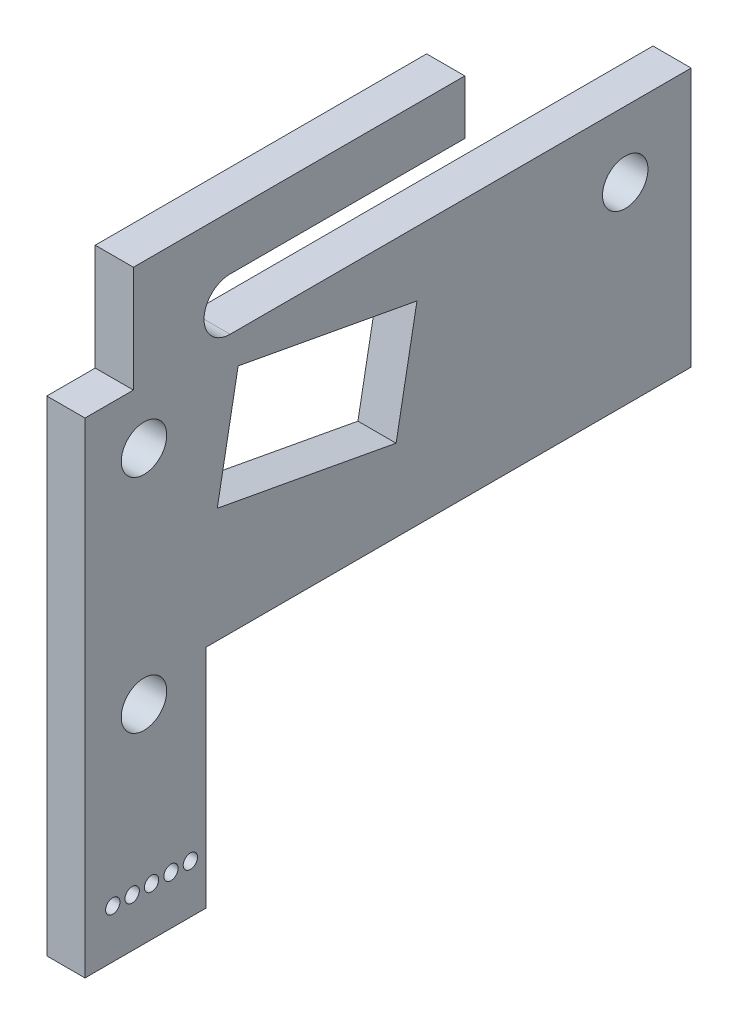
SolidWorks part; units mm, degrees
material "Hardboard"
ref_plane "Front Plane" through (0, 0, 0) normal (0, 0, 1) x (1, 0, 0)
ref_plane "Top Plane" through (0, 0, 0) normal (0, 1, 0) x (1, 0, 0)
ref_plane "Right Plane" through (0, 0, 0) normal (1, 0, 0) x (0, 0, -1)
sketch "Sketch1" plane through (0, 0, 0) normal (1, 0, 0) x (0, 0, -1)
  line L0 (-56.5904, 6.9096) -> (-51.5186, 6.9096)
  line L1 (-56.5904, 6.9096) -> (-56.5904, -43.8904)
  line L2 (-56.5904, -43.8904) -> (-43.8904, -43.8904)
  line L3 (-43.8904, -43.8904) -> (-43.8904, -20.2221)
  line L4 (-43.8904, -20.2221) -> (6.9096, -20.2221)
  line L5 (6.9096, -20.2221) -> (6.9096, 6.9096)
  line L6 (0, 6.9096) -> (0, 0) construction
  line L7 (6.9096, 0) -> (0, 0) construction
  line L8 (-40.5479, 3.6124) -> (-21.8156, 0.1475)
  line L9 (-40.5479, 3.6124) -> (-42.7334, -8.2033)
  line L10 (-21.8156, 0.1475) -> (-24.0012, -11.6682)
  line L11 (-42.7334, -8.2033) -> (-24.0012, -11.6682)
  line L12 (-45.553, -38.8104) -> (-47.585, -38.8104) construction
  line L13 (-41.3883, 12.3738) -> (-16.804, 12.3738)
  line L14 (-16.804, 12.3738) -> (-16.804, 18.0537)
  line L15 (-16.804, 18.0537) -> (-51.5186, 18.0537)
  line L16 (-51.5186, 18.0537) -> (-51.5186, 6.9096)
  line L17 (-41.3883, 6.9096) -> (6.9096, 6.9096)
  line L18 (-43.4375, 2.8639) -> (-40.7623, 15.279) construction
  circle A0 centre (0, 0) radius 2.3813
  circle A1 centre (-45.553, -38.8104) radius 0.75
  circle A2 centre (-47.585, -38.8104) radius 0.75
  circle A3 centre (-49.617, -38.8104) radius 0.75
  circle A4 centre (-51.649, -38.8104) radius 0.75
  circle A5 centre (-50.4101, -22.1372) radius 2.3812
  circle A6 centre (-50.4101, 1.0794) radius 2.3812
  circle A7 centre (-53.681, -38.8104) radius 0.75
  arc A8 (-41.3883, 6.9096) -> (-41.3883, 12.3738) centre (-41.3883, 9.6417) cw
  dimension "D1" = 4.7625
  dimension "D2" = 1.5
  dimension "D3" = 5.08
  dimension "D5" = 2.032
  dimension "D6" = 19.05
  dimension "D4" = 5
extrude "Boss-Extrude1" add sketch "Sketch1" along normal mid plane 4
